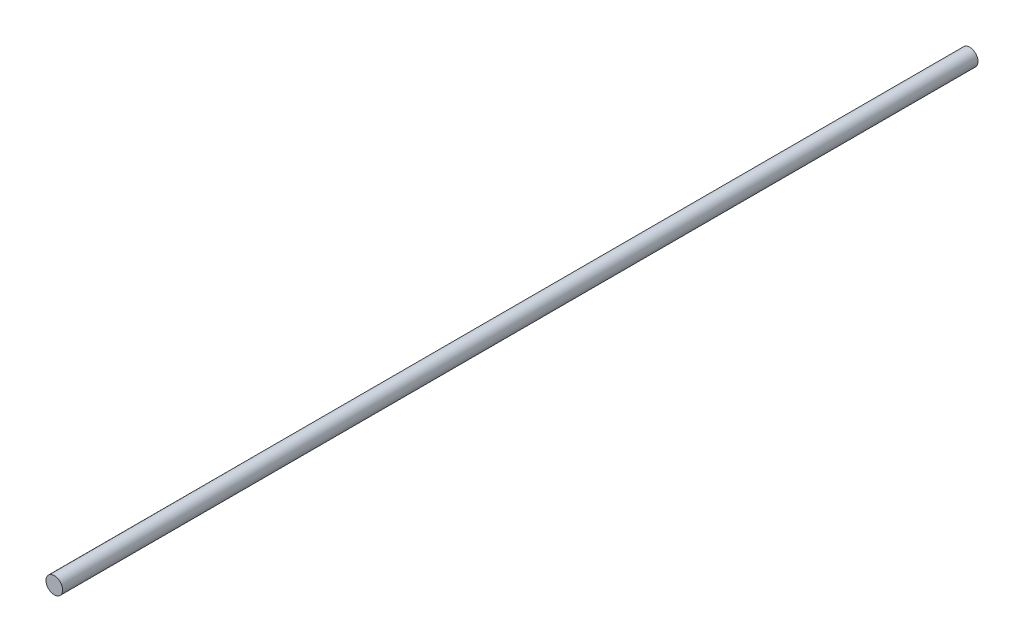
SolidWorks part; units mm, degrees
ref_plane "Plan de face" through (0, 0, 0) normal (0, 0, 1) x (1, 0, 0)
ref_plane "Plan de dessus" through (0, 0, 0) normal (0, 1, 0) x (1, 0, 0)
ref_plane "Plan de droite" through (0, 0, 0) normal (1, 0, 0) x (0, 0, -1)
sketch "Esquisse1" plane through (0, 0, 0) normal (0, 0, 1) x (1, 0, 0)
  circle A0 centre (0, 0) radius 3
  dimension "D1" = 6
extrude "Boss.-Extru.1" add sketch "Esquisse1" along normal blind 330
